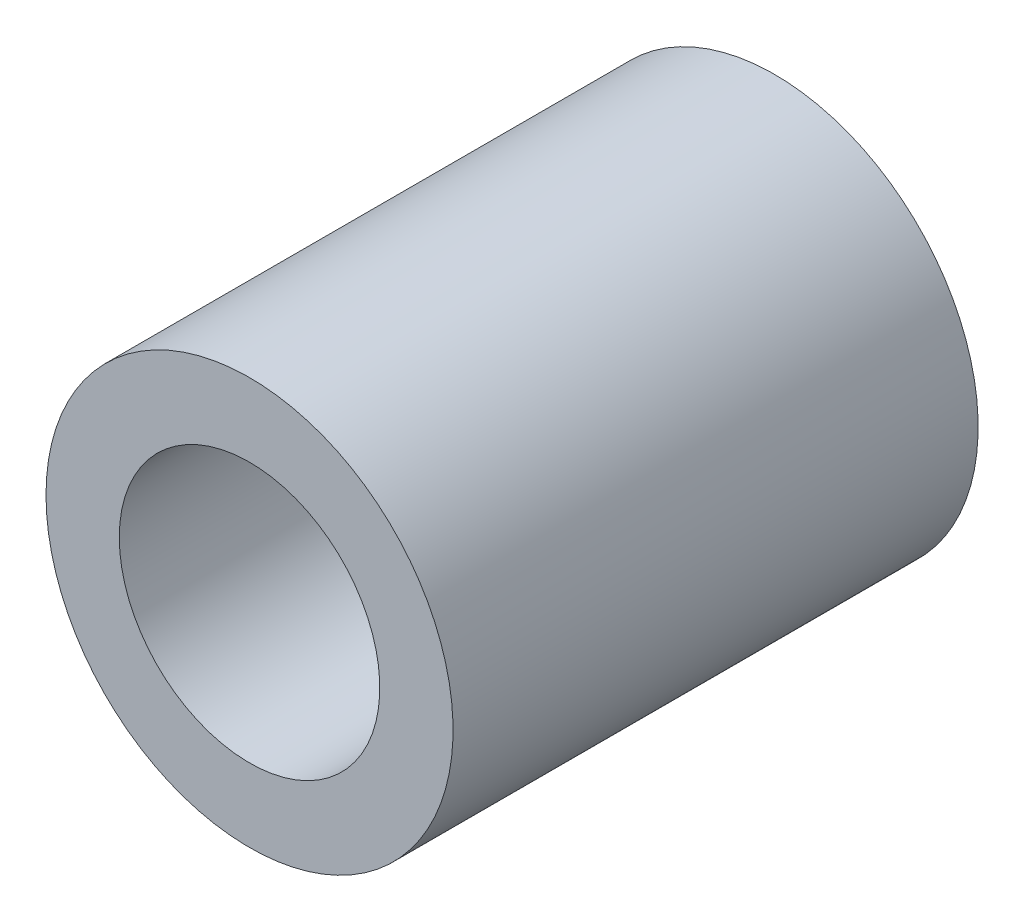
SolidWorks part; units mm, degrees
ref_plane "Front Plane" through (0, 0, 0) normal (0, 0, 1) x (1, 0, 0)
ref_plane "Top Plane" through (0, 0, 0) normal (0, 1, 0) x (1, 0, 0)
ref_plane "Right Plane" through (0, 0, 0) normal (1, 0, 0) x (0, 0, -1)
sketch "Sketch1" plane through (0, 0, 0) normal (0, 0, 1) x (1, 0, 0)
  circle A0 centre (0, 0) radius 1.6
  circle A2 centre (0, 0) radius 2.5
  dimension "D1" = 5
  dimension "D2" = 3.2
extrude "Boss-Extrude1" add sketch "Sketch1" along normal up to surface (6.45 mm away)
